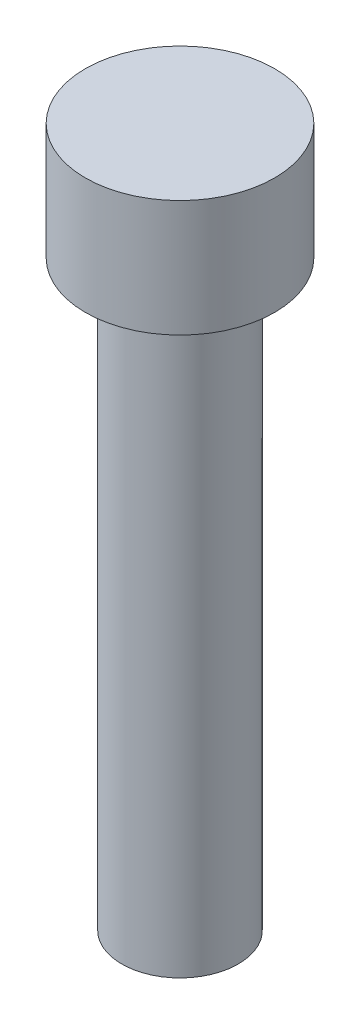
SolidWorks part; units mm, degrees
ref_plane "Front Plane" through (0, 0, 0) normal (0, 0, 1) x (1, 0, 0)
ref_plane "Top Plane" through (0, 0, 0) normal (0, 1, 0) x (1, 0, 0)
ref_plane "Right Plane" through (0, 0, 0) normal (1, 0, 0) x (0, 0, -1)
sketch "Sketch1" plane through (0, 0, 0) normal (0, 0, 1) x (1, 0, 0)
  line L0 (0, 0) -> (0, 48)
  line L1 (0, 48) -> (6.5, 48)
  line L2 (6.5, 48) -> (6.5, 40)
  line L3 (6.5, 40) -> (4, 40)
  line L4 (4, 40) -> (4, 0)
  line L5 (4, 0) -> (0, 0)
  dimension "D1" = 4
  dimension "D2" = 6.5
  dimension "D3" = 8
  dimension "D4" = 40
revolve "Revolve1" add sketch "Sketch1" angle 360 about L0
